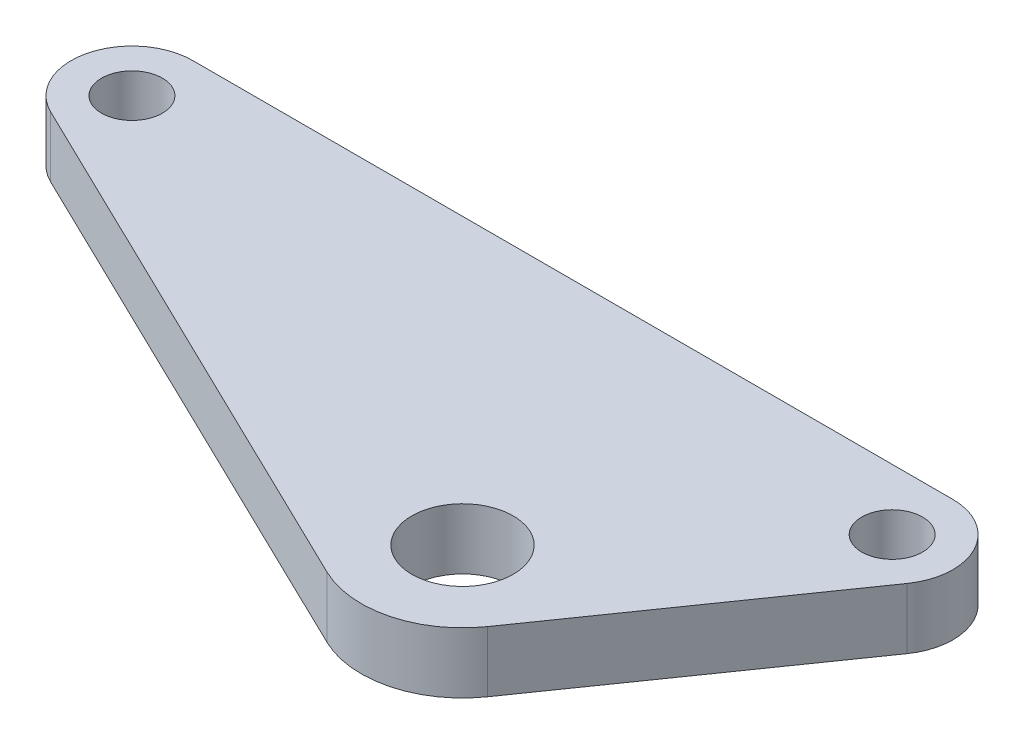
SolidWorks part; units mm, degrees
ref_plane "前视基准面" through (0, 0, 0) normal (0, 0, 1) x (1, 0, 0)
ref_plane "上视基准面" through (0, 0, 0) normal (0, 1, 0) x (1, 0, 0)
ref_plane "右视基准面" through (0, 0, 0) normal (1, 0, 0) x (0, 0, -1)
sketch "草图1" plane through (0, 0, 0) normal (0, 1, 0) x (1, 0, 0)
  line L0 (0, 0) -> (75, 0) construction
  line L1 (75, 0) -> (54.7067, -22.0948) construction
  line L2 (54.7067, -22.0948) -> (0, 0) construction
  line L3 (-2.6189, -5.3983) -> (50.3418, -31.0919)
  line L4 (62.9078, -27.8169) -> (79.9207, -3.4332)
  line L5 (0, 6) -> (75, 6)
  circle A0 centre (54.7067, -22.0948) radius 5
  circle A1 centre (75, 0) radius 3
  circle A2 centre (0, 0) radius 3
  arc A3 (0, 6) -> (-2.6189, -5.3983) centre (0, 0) ccw
  arc A4 (79.9207, -3.4332) -> (75, 6) centre (75, 0) ccw
  arc A5 (50.3418, -31.0919) -> (62.9078, -27.8169) centre (54.7067, -22.0948) ccw
  dimension "D4" = 6
  dimension "D5" = 10
  dimension "D6" = 12
  dimension "D7" = 20
  dimension "D1" = 75
  dimension "D2" = 59
  dimension "D3" = 30
extrude "凸台-拉伸1" add sketch "草图1" along normal mid plane 6
